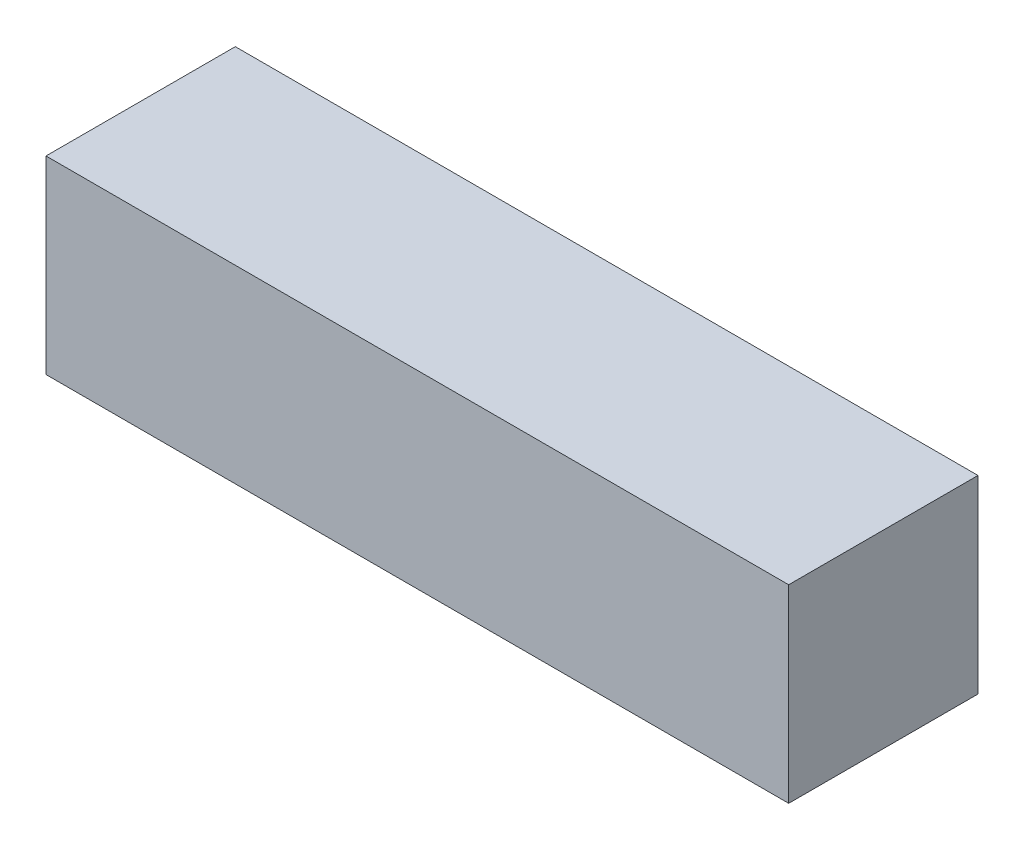
SolidWorks part; units mm, degrees
ref_plane "Front Plane" through (0, 0, 0) normal (0, 0, 1) x (1, 0, 0)
ref_plane "Top Plane" through (0, 0, 0) normal (0, 1, 0) x (1, 0, 0)
ref_plane "Right Plane" through (0, 0, 0) normal (1, 0, 0) x (0, 0, -1)
sketch "Sketch1" plane through (0, 0, 0) normal (0, 1, 0) x (1, 0, 0)
  line L1 (0, 0) -> (102, 0)
  line L2 (0, 0) -> (0, 26)
  line L3 (0, 26) -> (102, 26)
  line L4 (102, 0) -> (102, 26)
  dimension "D1" = 102
  dimension "D2" = 26
extrude "Boss-Extrude1" add sketch "Sketch1" along normal blind 26
